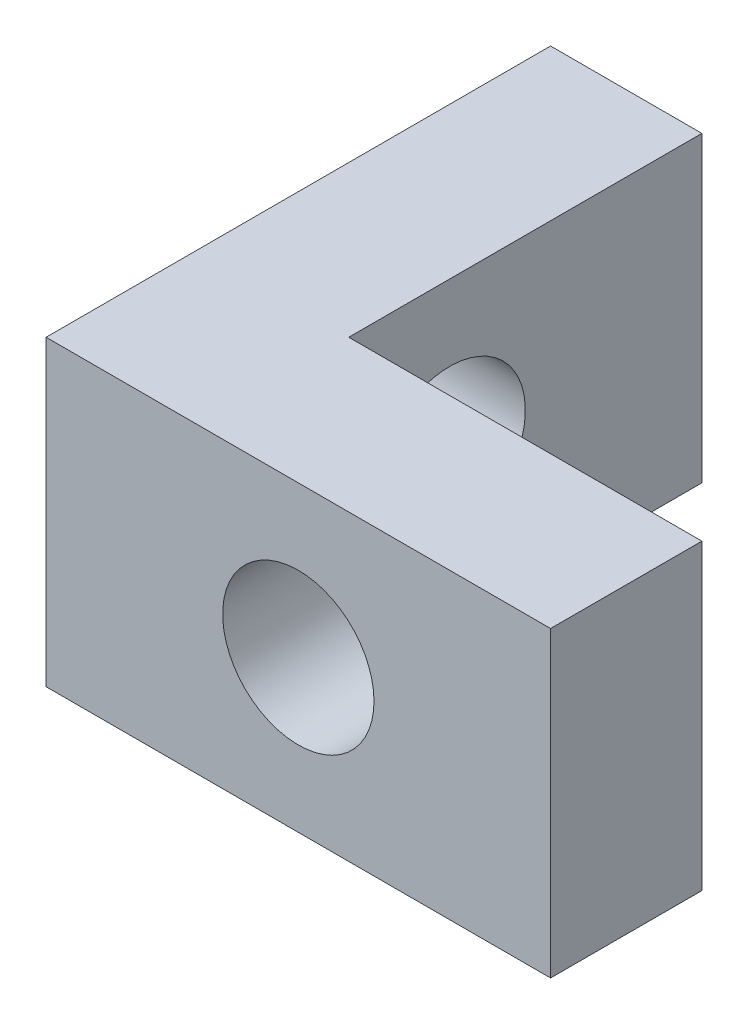
SolidWorks part; units mm, degrees
material "普通碳钢"
ref_plane "前视基准面" through (0, 0, 0) normal (0, 0, 1) x (1, 0, 0)
ref_plane "上视基准面" through (0, 0, 0) normal (0, 1, 0) x (1, 0, 0)
ref_plane "右视基准面" through (0, 0, 0) normal (1, 0, 0) x (0, 0, -1)
other "Configuration Table"
sketch "草图1" plane through (0, 0, 0) normal (0, 1, 0) x (1, 0, 0)
  line L1 (0, 0) -> (10, 0)
  line L2 (0, 0) -> (0, 10)
  line L3 (0, 10) -> (3, 10)
  line L4 (10, 0) -> (10, 3)
  line L7 (10, 3) -> (3, 3)
  line L8 (3, 10) -> (3, 3)
  dimension "D1" = 10
  dimension "D2" = 10
  dimension "D3" = 7
  dimension "D4" = 7
extrude "凸台-拉伸1" add sketch "草图1" along normal blind 6
sketch "草图2" plane through (0, 0, 0) normal (0, 0, 1) x (1, 0, 0)
  line L0 (0, 6) -> (0, 0) construction
  line L1 (0, 0) -> (10, 0) construction
  circle A0 centre (5, 3) radius 1.5
  dimension "D3" = 3
  dimension "D1" = 5
  dimension "D2" = 3
extrude "切除-拉伸1" cut sketch "草图2" against normal blind 6
sketch "草图3" plane through (0, 0, 0) normal (-1, 0, 0) x (0, 0, 1)
  line L0 (0, 6) -> (0, 0) construction
  line L1 (-10, 0) -> (0, 0) construction
  circle A0 centre (-5, 3) radius 1.5
  dimension "D3" = 3
  dimension "D1" = 5
  dimension "D2" = 3
extrude "切除-拉伸2" cut sketch "草图3" against normal blind 6
